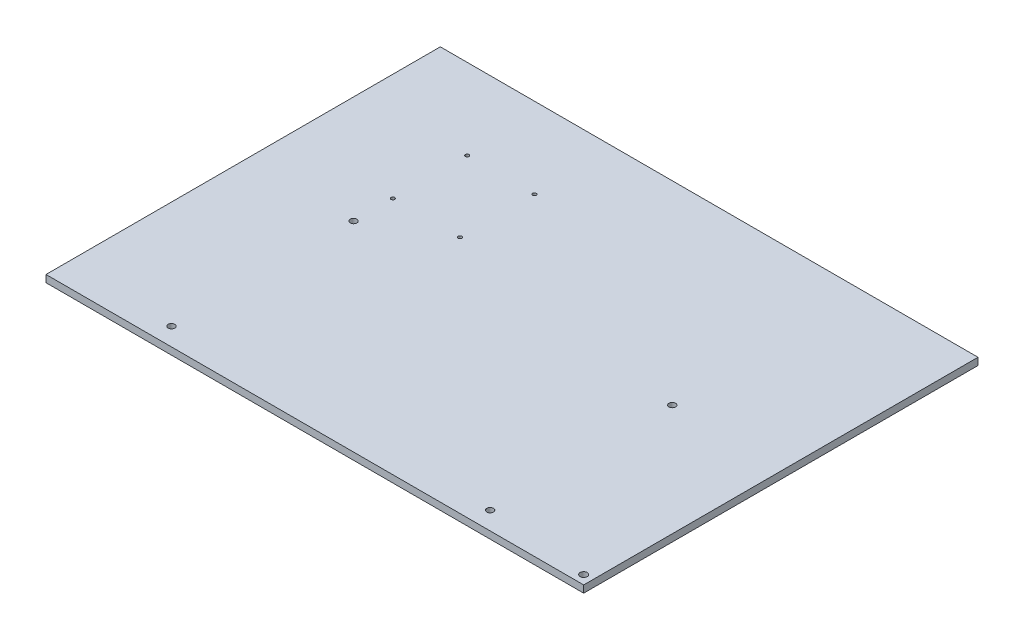
SolidWorks part; units mm, degrees
ref_plane "Front Plane" through (0, 0, 0) normal (0, 0, 1) x (1, 0, 0)
ref_plane "Top Plane" through (0, 0, 0) normal (0, 1, 0) x (1, 0, 0)
ref_plane "Right Plane" through (0, 0, 0) normal (1, 0, 0) x (0, 0, -1)
sketch "Sketch1" plane through (0, 0, 0) normal (0, 1, 0) x (1, 0, 0)
  line L1 (150, -110) -> (-150, -110)
  line L2 (150, -110) -> (150, 110)
  line L3 (150, 110) -> (-150, 110)
  line L4 (-150, -110) -> (-150, 110)
  line L5 (150, -110) -> (-150, 110) construction
  line L6 (150, 110) -> (-150, -110) construction
  point P0 (0, 0)
  dimension "D1" = 300
  dimension "D2" = 220
extrude "Boss-Extrude1" add sketch "Sketch1" along normal blind 4
sketch "Sketch2" plane through (0, 0, 0) normal (0, 1, 0) x (1, 0, 0)
  line L0 (-90, -100) -> (87.8, -100) construction
  line L1 (-90, 1.6) -> (87.8, 1.6) construction
  line L2 (-1.1, -100) -> (-1.1, 1.6) construction
  line L3 (-1.1, -49.2) -> (-70.6928, -49.2) construction
  line L4 (-150, 110) -> (-150, -110) construction
  line L5 (-150, -110) -> (150, -110) construction
  circle A0 centre (-90, -100) radius 1.85
  circle A1 centre (87.8, -100) radius 1.85
  circle A2 centre (87.8, 1.6) radius 1.85
  circle A3 centre (-90, 1.6) radius 1.85
  dimension "D1" = 3.7
  dimension "D2" = 177.8
  dimension "D3" = 101.6
  dimension "D4" = 60
  dimension "D5" = 10
extrude "Cut-Extrude1" cut sketch "Sketch2" against normal through all both and the other way through all
sketch "Sketch3" plane through (0, 4, 0) normal (0, 1, 0) x (1, 0, 0)
  line L0 (-93.8548, 44.25) -> (-48.8548, 44.25) construction
  line L1 (150, 110) -> (-150, 110) construction
  line L2 (-150, 110) -> (-150, -110) construction
  circle A0 centre (-90, 65) radius 1
  circle A1 centre (-52.5, 65) radius 1
  circle A2 centre (-52.5, 23.5) radius 1
  circle A3 centre (-90, 23.5) radius 1
  point P10 (0, 0)
  point P11 (0, 0)
  dimension "D1" = 2
  dimension "D2" = 41.5
  dimension "D3" = 37.5
  dimension "D4" = 45
  dimension "D5" = 60
extrude "Cut-Extrude2" cut sketch "Sketch3" against normal through all both and the other way through all
sketch "Sketch4" plane through (0, 4, 0) normal (0, 1, 0) x (1, 0, 0)
  line L0 (-150, -110) -> (150, -110) construction
  line L1 (150, -110) -> (150, 110) construction
  circle A0 centre (145, -105) radius 2
  dimension "D1" = 4
  dimension "D2" = 5
  dimension "D3" = 5
extrude "Cut-Extrude3" cut sketch "Sketch4" against normal through all
